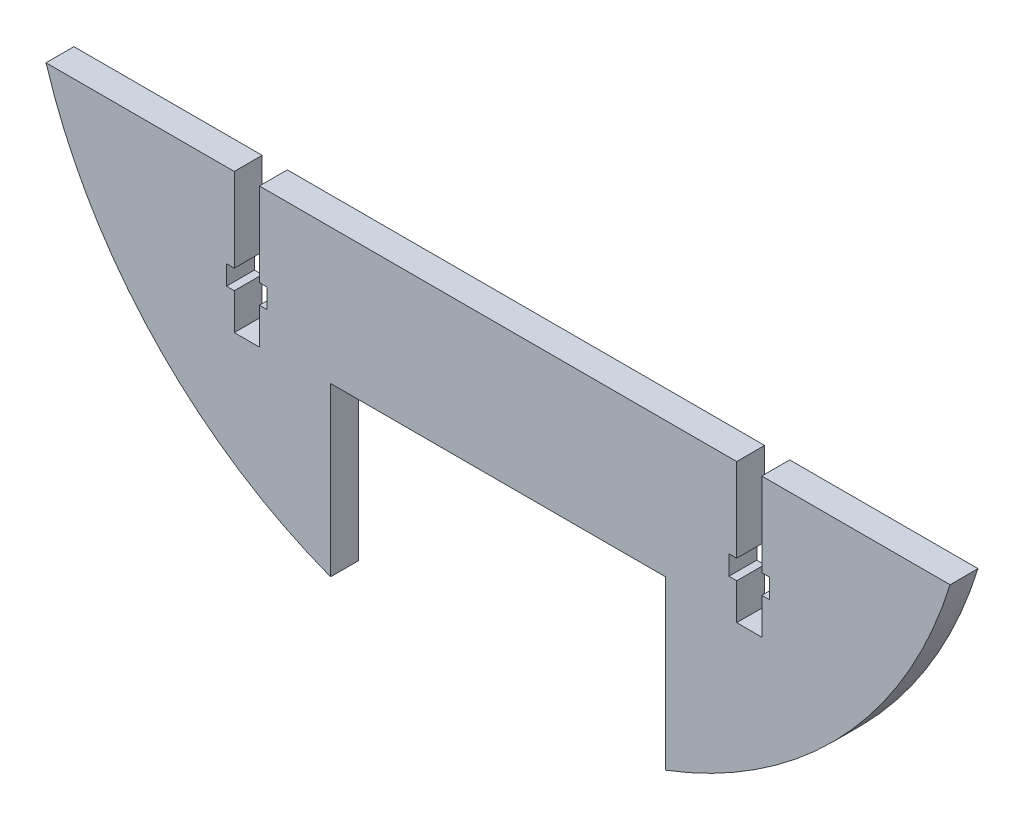
SolidWorks part; units mm, degrees
ref_plane "前视基准面" through (0, 0, 0) normal (0, 0, 1) x (1, 0, 0)
ref_plane "上视基准面" through (0, 0, 0) normal (0, 1, 0) x (1, 0, 0)
ref_plane "右视基准面" through (0, 0, 0) normal (1, 0, 0) x (0, 0, -1)
sketch "草图1" plane through (0, 0, 0) normal (0, 0, 1) x (1, 0, 0)
  line L0 (-80.9788, -25) -> (-47.25, -25)
  line L1 (0, 0) -> (0, -49.2626) construction
  line L2 (-47.25, -40) -> (-47.25, -25)
  line L3 (-47.25, -43.5) -> (-47.25, -50)
  line L4 (-47.25, -50) -> (-42.75, -50)
  line L5 (-45, -21.4618) -> (-45, -48.0469) construction
  line L6 (-47.25, -40) -> (-48.65, -40)
  line L7 (-48.65, -40) -> (-48.65, -43.5)
  line L8 (-48.65, -43.5) -> (-47.25, -43.5)
  line L9 (-42.75, -43.5) -> (-42.75, -50)
  line L10 (-41.35, -43.5) -> (-42.75, -43.5)
  line L11 (-41.35, -40) -> (-41.35, -43.5)
  line L12 (-42.75, -40) -> (-41.35, -40)
  line L13 (-42.75, -25) -> (-42.75, -40)
  line L25 (-42.75, -25) -> (42.75, -25)
  line L26 (47.25, -25) -> (80.9788, -25)
  line L27 (45, -15.6613) -> (45, -50.568) construction
  line L28 (42.75, -25) -> (42.75, -40)
  line L29 (42.75, -40) -> (41.35, -40)
  line L30 (41.35, -40) -> (41.35, -43.5)
  line L31 (41.35, -43.5) -> (42.75, -43.5)
  line L32 (42.75, -43.5) -> (42.75, -50)
  line L33 (42.75, -50) -> (47.25, -50)
  line L34 (47.25, -43.5) -> (47.25, -50)
  line L35 (48.65, -43.5) -> (47.25, -43.5)
  line L36 (48.65, -40) -> (48.65, -43.5)
  line L37 (47.25, -40) -> (48.65, -40)
  line L38 (47.25, -25) -> (47.25, -40)
  line L39 (-30, -79.2626) -> (-30, -49.2626)
  line L40 (-30, -49.2626) -> (30, -49.2626)
  line L41 (30, -79.2626) -> (30, -49.2626)
  line L42 (0, -85) -> (0, -103.1779) construction
  arc A0 (-80.9788, -25) -> (-30, -79.2626) centre (0, 0) ccw
  arc A1 (30, -79.2626) -> (80.9788, -25) centre (0, 0) ccw
  point P11 (-45, -50)
  point P12 (-45, -50)
  point P31 (45, -50)
  point P40 (0, -49.2626)
  dimension "D1" = 169.5
  dimension "D2" = 25
  dimension "D3" = 45
  dimension "D4" = 4.5
  dimension "D5" = 3.5
  dimension "D6" = 7.3
  dimension "D7" = 25
  dimension "D8" = 15
  dimension "D9" = 45
  dimension "D10" = 25
  dimension "D11" = 3.5
  dimension "D12" = 15
  dimension "D13" = 7.3
  dimension "D14" = 60
  dimension "D15" = 30
extrude "凸台-拉伸1" add sketch "草图1" along normal blind 5
